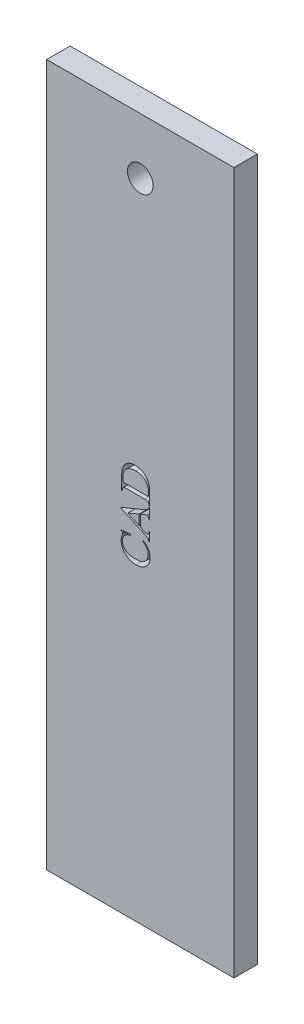
SolidWorks part; units mm, degrees
ref_plane "Front Plane" through (0, 0, 0) normal (0, 0, 1) x (1, 0, 0)
ref_plane "Top Plane" through (0, 0, 0) normal (0, 1, 0) x (1, 0, 0)
ref_plane "Right Plane" through (0, 0, 0) normal (1, 0, 0) x (0, 0, -1)
sketch "Sketch1" plane through (0, 0, 0) normal (0, 1, 0) x (1, 0, 0)
  line L1 (-20, 2.5) -> (20, 2.5)
  line L2 (-20, 2.5) -> (-20, -2.5)
  line L3 (-20, -2.5) -> (20, -2.5)
  line L4 (20, 2.5) -> (20, -2.5)
  line L5 (-20, 2.5) -> (20, -2.5) construction
  line L6 (-20, -2.5) -> (20, 2.5) construction
  point P0 (0, 0)
  dimension "D1" = 40
  dimension "D2" = 5
extrude "Boss-Extrude1" add sketch "Sketch1" along normal blind 150
sketch "Sketch3" plane through (0, 0, 2.5) normal (0, 0, 1) x (1, 0, 0)
  line L0 (2, 29.2658) -> (2, 121.12) construction
  line L3 (20, 150) -> (20, 0) construction
  text T0 "CAD" font "Times New Roman" height 6
  point P2 (0, 121.12)
  dimension "D1" = 18
extrude "Cut-Extrude1" cut sketch "Sketch3" against normal blind 5
sketch "Sketch4" plane through (0, 0, -2.5) normal (0, 0, -1) x (-1, 0, 0)
  line L0 (-20, 150) -> (20, 150) construction
  circle A0 centre (0, 138) radius 2.75
  point P4 (0, 0)
  dimension "D1" = 5.5
  dimension "D2" = 12
extrude "Cut-Extrude2" cut sketch "Sketch4" against normal through all
